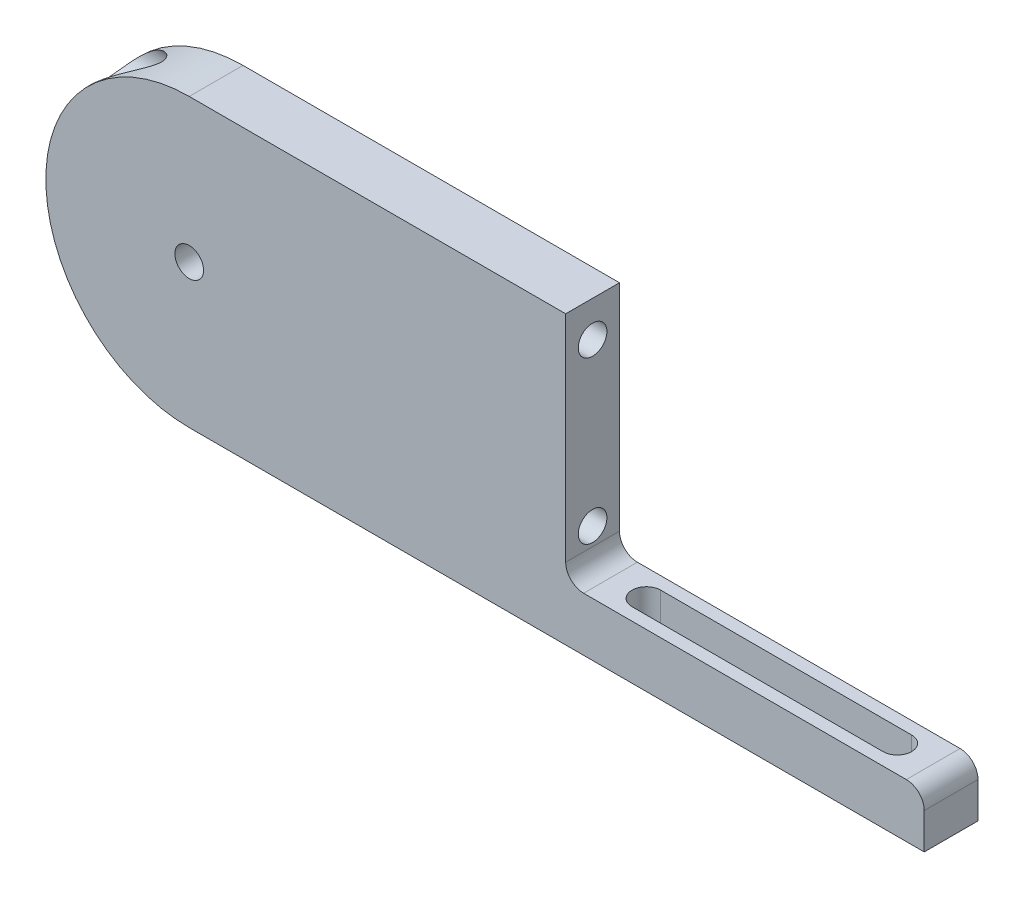
SolidWorks part; units mm, degrees
material "3.3549 (EN-AW 5182)"
ref_plane "Piano frontale" through (0, 0, 0) normal (0, 0, 1) x (1, 0, 0)
ref_plane "Piano superiore" through (0, 0, 0) normal (0, 1, 0) x (1, 0, 0)
ref_plane "Piano destro" through (0, 0, 0) normal (1, 0, 0) x (0, 0, -1)
sketch "Schizzo1" plane through (0, 0, 0) normal (0, 0, 1) x (1, 0, 0)
  line L0 (0, 0) -> (105, 0) construction
  line L1 (0, 40) -> (105, 40)
  line L3 (0, -40) -> (105, -40)
  line L4 (105, 40) -> (105, -40)
  arc A0 (0, 40) -> (0, -40) centre (0, 0) ccw
  dimension "D2" = 80
  dimension "D3" = 105
extrude "Estrusione1" add sketch "Schizzo1" along normal mid plane 15
sketch "Schizzo2" plane through (0, 0, 7.5) normal (0, 0, 1) x (1, 0, 0)
  circle A0 centre (0, 0) radius 4
  dimension "D1" = 8
extrude "Taglio-Estrusione1" cut sketch "Schizzo2" against normal blind 15
sketch "Schizzo4" plane through (0, 0, -7.5) normal (0, 0, 1) x (1, 0, 0)
  circle A0 centre (0, 0) radius 6.75
  dimension "D1" = 13.5
extrude "Taglio-Estrusione3" cut sketch "Schizzo4" along normal blind 8.5
sketch "Schizzo11" plane through (105, 0, 0) normal (1, 0, 0) x (0, 0, -1)
  line L0 (7.5, -40) -> (7.5, 40) construction
  line L1 (-7.5, -40) -> (7.5, -40)
  line L2 (-7.5, -40) -> (-7.5, -25)
  line L3 (-7.5, -25) -> (7.5, -25)
  line L4 (7.5, -40) -> (7.5, -25)
  dimension "D1" = 15
extrude "Estrusione3" add sketch "Schizzo11" along normal blind 100
fillet "Raccordo2" radius 5 2 edges at (205, -25, 0)
sketch "Schizzo13" plane through (105, 0, 0) normal (1, 0, 0) x (0, 0, -1)
  line L0 (0, 52.9681) -> (0, -49.039) construction
  line L1 (19.9286, 0) -> (-23.5945, 0) construction
  circle A0 centre (0, -15) radius 4
  circle A1 centre (0, 30) radius 4
  dimension "D2" = 8
  dimension "D3" = 8
  dimension "D1" = 15
  dimension "D4" = 30
extrude "Taglio-Estrusione4" cut sketch "Schizzo13" against normal through all
ref_plane "Piano1" through (85, 0, 0) normal (1, 0, 0) x (0, 0, -1)
sketch "Schizzo14" plane through (85, 0, 0) normal (1, 0, 0) x (0, 0, -1)
  circle A0 centre (0, 30) radius 7
  circle A1 centre (0, -15) radius 7
  dimension "D1" = 14
  dimension "D2" = 14
extrude "Taglio-Estrusione5" cut sketch "Schizzo14" against normal through all
sketch "Schizzo15" plane through (0, -40, 0) normal (0, -1, 0) x (1, 0, 0)
  line L0 (-47.8471, 0) -> (151.0204, 0) construction
  line L1 (205, 7.5) -> (205, -7.5) construction
  line L2 (120, 4) -> (190, 4)
  line L4 (120, -4) -> (190, -4)
  arc A0 (120, 4) -> (120, -4) centre (120, 0) ccw
  arc A1 (190, -4) -> (190, 4) centre (190, 0) ccw
  dimension "D1" = 15
  dimension "D2" = 70
  dimension "D3" = 8
extrude "Taglio-Estrusione6" cut sketch "Schizzo15" against normal blind 100
